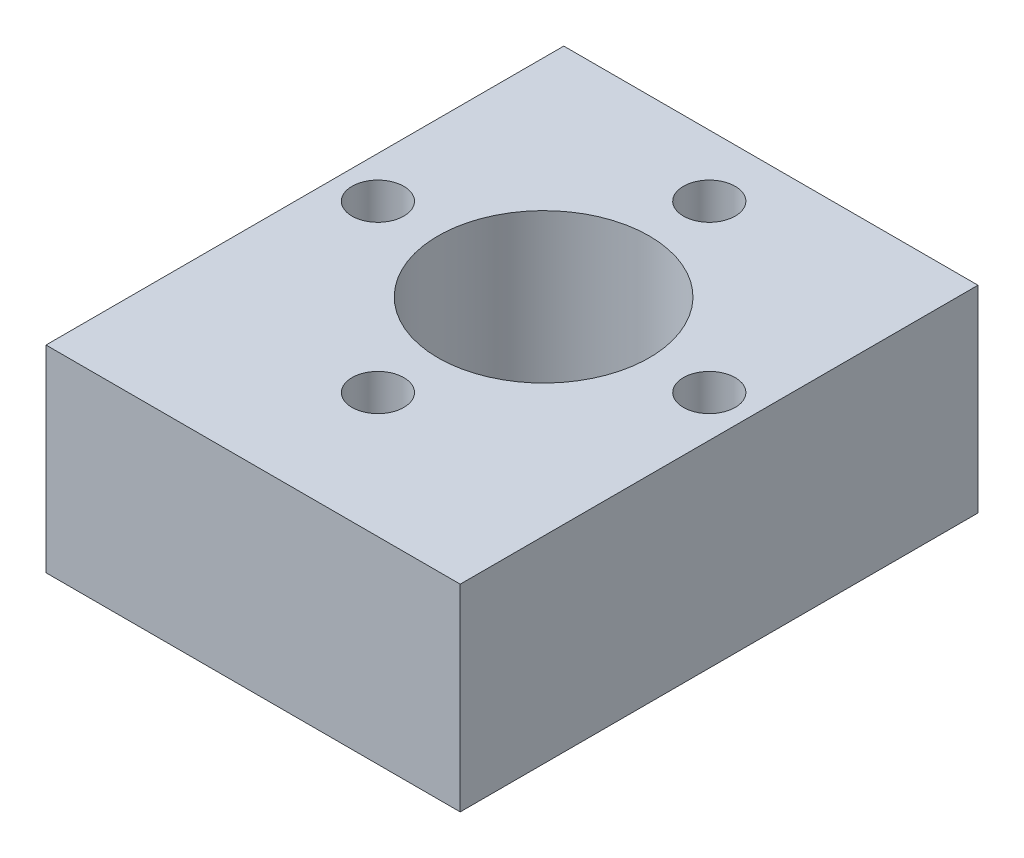
SolidWorks part; units mm, degrees
ref_plane "Front Plane" through (0, 0, 0) normal (0, 0, 1) x (1, 0, 0)
ref_plane "Top Plane" through (0, 0, 0) normal (0, 1, 0) x (1, 0, 0)
ref_plane "Right Plane" through (0, 0, 0) normal (1, 0, 0) x (0, 0, -1)
sketch "Sketch1" plane through (0, 0, 0) normal (0, 1, 0) x (1, 0, 0)
  line L1 (-10, -12.5) -> (10, -12.5)
  line L2 (-10, -12.5) -> (-10, 12.5)
  line L3 (-10, 12.5) -> (10, 12.5)
  line L4 (10, -12.5) -> (10, 12.5)
  line L5 (-10, -12.5) -> (10, 12.5) construction
  line L6 (-10, 12.5) -> (10, -12.5) construction
  circle A0 centre (0, 1.5262) radius 5.1
  point P0 (0, 1.5262)
  point P8 (2.552, -0.093)
  point P10 (0, 0)
  point P11 (0, 0)
  point P12 (-18.8926, -2.7762)
  point P14 (0, 0)
  point P15 (0, 2.9432)
  dimension "D1" = 10.2
  dimension "D2" = 20
  dimension "D3" = 25
  dimension "D4" = 1.5262
extrude "Boss-Extrude1" add sketch "Sketch1" along normal blind 9.525 contours L1 L4 L3 L2 A0
sketch "Sketch2" plane through (0, 9.525, 0) normal (0, 1, 0) x (1, 0, 0)
  circle A0 centre (0, 1.5262) radius 8 construction
  point P2 (0, 9.5262)
  point P4 (8, 1.5262)
  point P5 (0, -6.4738)
  point P6 (-8, 1.5262)
  dimension "D1" = 8
hole_wizard "Tap Drill for M3x0.5 Tap1" positions "Sketch2" profile "Sketch3" hole size "M3x0.5" standard "ANSI Metric" end condition through all
sketch "Sketch3" plane through (-8, 9.525, -1.5262) normal (1, 0, 0) x (0, 0, 1)
  line L0 (0, 0) -> (0, 9.525)
  line L1 (0, 9.525) -> (1.25, 9.525)
  line L2 (1.25, 9.525) -> (1.25, 0)
  line L5 (1.25, 0) -> (0, 0)
  line L11 (0, -6.35) -> (0, 107.95) construction
  dimension "Thru Hole Dia." = 2.5
  dimension "Thru Hole Depth" = 9.525
sketch "Sketch4" plane through (0, 0, -12.5) normal (0, 0, -1) x (-1, 0, 0)
  line L0 (0, 0) -> (0, 9.525) construction
  line L1 (10, 9.525) -> (-10, 9.525) construction
  line L9 (-7, 4.7625) -> (7, 4.7625) construction
  point P5 (0, 4.7625)
  point P47 (0, 4.7625)
  dimension "D1" = 14
hole_wizard "Tap Drill for M3x0.5 Tap3" positions "Sketch7" profile "Sketch8" hole size "M3x0.5" standard "ANSI Metric"
sketch "Sketch7" plane through (0, 0, -12.5) normal (0, 0, -1) x (-1, 0, 0)
  point P0 (-7, 4.7625)
  point P3 (7, 4.7625)
sketch "Sketch8" plane through (7, 4.7625, -12.5) normal (1, 0, 0) x (0, 1, 0)
  line L0 (0, 0) -> (0, 6.7511)
  line L1 (0, 6.7511) -> (1.25, 6)
  line L2 (1.25, 6) -> (1.25, 0)
  line L5 (1.25, 0) -> (0, 0)
  line L10 (0, 6.7511) -> (-1.25, 6) construction
  line L11 (0, -6.35) -> (0, 107.95) construction
  dimension "Hole Dia." = 2.5
  dimension "Hole Depth" = 6
  dimension "Drill Angle" = 118
